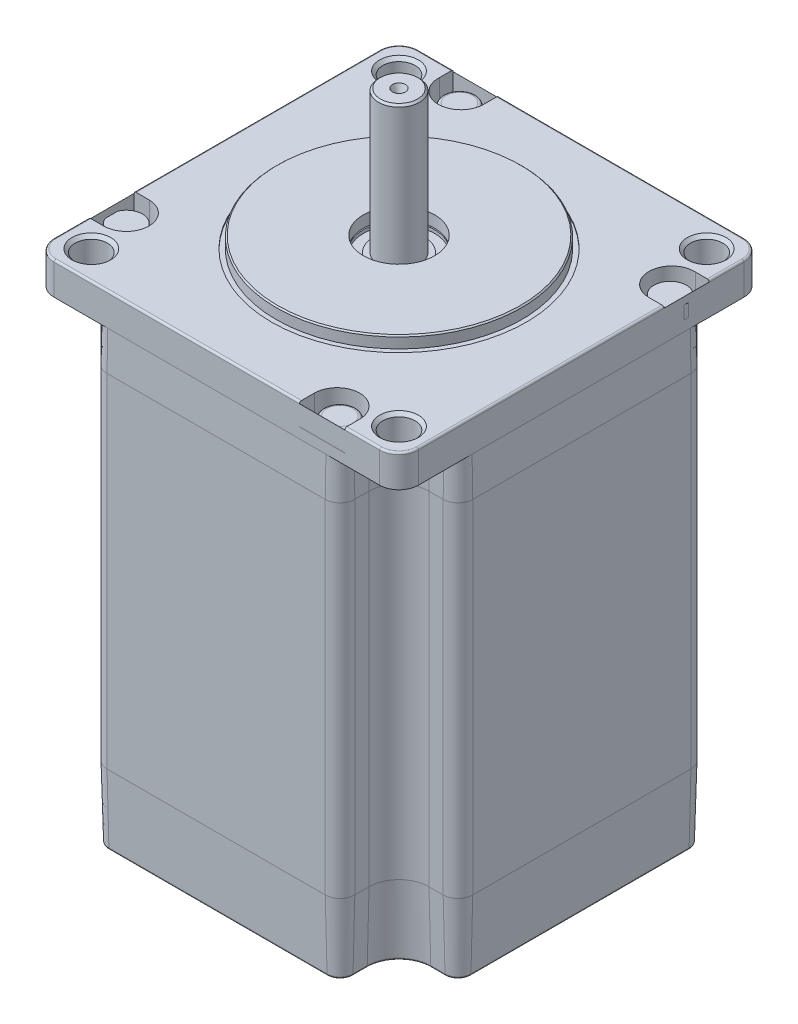
SolidWorks part; units mm, degrees
ref_plane "Спереди" through (0, 0, 0) normal (0, 0, 1) x (1, 0, 0)
ref_plane "Сверху" through (0, 0, 0) normal (0, 1, 0) x (1, 0, 0)
ref_plane "Справа" through (0, 0, 0) normal (1, 0, 0) x (0, 0, -1)
sketch "Эскиз1" plane through (0, 0, 0) normal (0, 1, 0) x (1, 0, 0)
  line L0 (0, 33.8984) -> (0, -32.5387) construction
  line L1 (-16.8775, 28) -> (16.8775, 28)
  line L2 (-28, 16.8775) -> (-28, -16.8775)
  line L3 (-16.8775, -28) -> (16.8775, -28)
  line L4 (28, 16.8775) -> (28, -16.8775)
  line L5 (-28, 28) -> (28, -28) construction
  line L6 (-28, -28) -> (28, 28) construction
  line L7 (-36.1503, 0) -> (41.6733, 0) construction
  line L8 (-18.8775, 23.8) -> (-18.8775, 26)
  line L9 (-23.8, 18.8775) -> (-26, 18.8775)
  line L10 (18.8775, 23.8) -> (18.8775, 26)
  line L11 (23.8, 18.8775) -> (26, 18.8775)
  line L12 (23.8, -18.8775) -> (26, -18.8775)
  line L13 (18.8775, -23.8) -> (18.8775, -26)
  line L14 (-18.8775, -23.8) -> (-18.8775, -26)
  line L15 (-23.8, -18.8775) -> (-26, -18.8775)
  arc A0 (-18.8775, 26) -> (-16.8775, 28) centre (-16.8775, 26) cw
  arc A2 (18.8775, 23.8) -> (23.8, 18.8775) centre (23.8, 23.8) ccw
  arc A3 (-18.8775, 23.8) -> (-23.8, 18.8775) centre (-23.8, 23.8) cw
  arc A5 (18.8775, -23.8) -> (23.8, -18.8775) centre (23.8, -23.8) cw
  arc A6 (-18.8775, -23.8) -> (-23.8, -18.8775) centre (-23.8, -23.8) ccw
  arc A9 (18.8775, 26) -> (16.8775, 28) centre (16.8775, 26) ccw
  arc A10 (26, 18.8775) -> (28, 16.8775) centre (26, 16.8775) cw
  arc A11 (26, -18.8775) -> (28, -16.8775) centre (26, -16.8775) ccw
  arc A12 (18.8775, -26) -> (16.8775, -28) centre (16.8775, -26) cw
  arc A13 (-18.8775, -26) -> (-16.8775, -28) centre (-16.8775, -26) ccw
  arc A14 (-26, -18.8775) -> (-28, -16.8775) centre (-26, -16.8775) cw
  arc A15 (-26, 18.8775) -> (-28, 16.8775) centre (-26, 16.8775) ccw
  point P0 (0, 0)
  point P36 (-18.8775, 28)
  point P39 (18.8775, 28)
  point P46 (18.8775, -28)
  point P49 (-18.8775, -28)
  point P52 (-28, -18.8775)
  point P55 (-28, 18.8775)
  dimension "D3" = 2
  dimension "D1" = 56
  dimension "D2" = 56
  dimension "D6" = 4.2
extrude "Бобышка-Вытянуть4" add sketch "Эскиз1" along normal blind 11 draft 1.5 draft outward yes
sketch "Эскиз8" plane through (0, 11, 0) normal (0, 1, 0) x (1, 0, 0)
  line L0 (-23.8, 19.1655) -> (-26, 19.1655) construction
  line L1 (-19.1655, 26) -> (-19.1655, 23.8) construction
  line L2 (16.8775, 28.288) -> (-16.8775, 28.288) construction
  line L3 (-28.288, 16.8775) -> (-28.288, -16.8775) construction
  line L4 (-26, -19.1655) -> (-23.8, -19.1655) construction
  line L5 (-19.1655, -23.8) -> (-19.1655, -26) construction
  line L6 (-16.8775, -28.288) -> (16.8775, -28.288) construction
  line L7 (19.1655, -26) -> (19.1655, -23.8) construction
  line L8 (23.8, -19.1655) -> (26, -19.1655) construction
  line L9 (28.288, -16.8775) -> (28.288, 16.8775) construction
  line L10 (26, 19.1655) -> (23.8, 19.1655) construction
  line L11 (19.1655, 23.8) -> (19.1655, 26) construction
  line L12 (-23.8, 19.1655) -> (-26, 19.1655)
  line L13 (-19.1655, 26) -> (-19.1655, 23.8)
  line L14 (16.8775, 28.288) -> (-16.8775, 28.288)
  line L15 (-28.288, 16.8775) -> (-28.288, -16.8775)
  line L16 (-26, -19.1655) -> (-23.8, -19.1655)
  line L17 (-19.1655, -23.8) -> (-19.1655, -26)
  line L18 (-16.8775, -28.288) -> (16.8775, -28.288)
  line L19 (19.1655, -26) -> (19.1655, -23.8)
  line L20 (23.8, -19.1655) -> (26, -19.1655)
  line L21 (28.288, -16.8775) -> (28.288, 16.8775)
  line L22 (26, 19.1655) -> (23.8, 19.1655)
  line L23 (19.1655, 23.8) -> (19.1655, 26)
  arc A0 (-26, 19.1655) -> (-28.288, 16.8775) centre (-26, 16.8775) ccw construction
  arc A1 (-23.8, 19.1655) -> (-19.1655, 23.8) centre (-23.8, 23.8) ccw construction
  arc A2 (-16.8775, 28.288) -> (-19.1655, 26) centre (-16.8775, 26) ccw construction
  arc A3 (-28.288, -16.8775) -> (-26, -19.1655) centre (-26, -16.8775) ccw construction
  arc A4 (-19.1655, -23.8) -> (-23.8, -19.1655) centre (-23.8, -23.8) ccw construction
  arc A5 (-19.1655, -26) -> (-16.8775, -28.288) centre (-16.8775, -26) ccw construction
  arc A6 (16.8775, -28.288) -> (19.1655, -26) centre (16.8775, -26) ccw construction
  arc A7 (23.8, -19.1655) -> (19.1655, -23.8) centre (23.8, -23.8) ccw construction
  arc A8 (26, -19.1655) -> (28.288, -16.8775) centre (26, -16.8775) ccw construction
  arc A9 (28.288, 16.8775) -> (26, 19.1655) centre (26, 16.8775) ccw construction
  arc A10 (19.1655, 23.8) -> (23.8, 19.1655) centre (23.8, 23.8) ccw construction
  arc A11 (19.1655, 26) -> (16.8775, 28.288) centre (16.8775, 26) ccw construction
  arc A12 (-26, 19.1655) -> (-28.288, 16.8775) centre (-26, 16.8775) ccw
  arc A13 (-23.8, 19.1655) -> (-19.1655, 23.8) centre (-23.8, 23.8) ccw
  arc A14 (-16.8775, 28.288) -> (-19.1655, 26) centre (-16.8775, 26) ccw
  arc A15 (-28.288, -16.8775) -> (-26, -19.1655) centre (-26, -16.8775) ccw
  arc A16 (-19.1655, -23.8) -> (-23.8, -19.1655) centre (-23.8, -23.8) ccw
  arc A17 (-19.1655, -26) -> (-16.8775, -28.288) centre (-16.8775, -26) ccw
  arc A18 (16.8775, -28.288) -> (19.1655, -26) centre (16.8775, -26) ccw
  arc A19 (23.8, -19.1655) -> (19.1655, -23.8) centre (23.8, -23.8) ccw
  arc A20 (26, -19.1655) -> (28.288, -16.8775) centre (26, -16.8775) ccw
  arc A21 (28.288, 16.8775) -> (26, 19.1655) centre (26, 16.8775) ccw
  arc A22 (19.1655, 23.8) -> (23.8, 19.1655) centre (23.8, 23.8) ccw
  arc A23 (19.1655, 26) -> (16.8775, 28.288) centre (16.8775, 26) ccw
extrude "Бобышка-Вытянуть9" add sketch "Эскиз8" along normal blind 53
fillet "Скругление2" radius 0.3 24 edges at (-24.9, 0, -18.8775) (-27.4142, 0, -18.2917) (-28, 0, 0) (-27.4142, 0, 18.2917) (-24.9, 0, 18.8775) (-20.3193, 0, 20.3193) (-18.8775, 0, 24.9) (-18.2917, 0, 27.4142) (0, 0, 28) (18.2917, 0, 27.4142) (18.8775, 0, 24.9) (20.3193, 0, 20.3193) (24.9, 0, 18.8775) (27.4142, 0, 18.2917) (28, 0, 0) (27.4142, 0, -18.2917) (24.9, 0, -18.8775) (20.3193, 0, -20.3193) (18.8775, 0, -24.9) (18.2917, 0, -27.4142) (0, 0, -28) (-18.2917, 0, -27.4142) (-18.8775, 0, -24.9) (-20.3193, 0, -20.3193)
sketch "Эскиз9" plane through (0, 0, 0) normal (0, -1, 0) x (1, 0, 0)
  circle A0 centre (0, 0) radius 5.5
  dimension "D1" = 11
extrude "Вырез-Вытянуть2" cut sketch "Эскиз9" against normal blind 2
sketch "Эскиз10" plane through (0, 0, 0) normal (0, -1, 0) x (1, 0, 0)
  circle A0 centre (0, 0) radius 12.5
  dimension "D1" = 25
extrude "Вырез-Вытянуть3" cut sketch "Эскиз10" against normal blind 3 from offset 2 offset against normal yes
sketch "Эскиз11" plane through (0, 5, 0) normal (0, -1, 0) x (1, 0, 0)
  circle A0 centre (0, 0) radius 5.6
  circle A1 centre (0, 0) radius 5.5
  dimension "D1" = 11.2
  dimension "D2" = 11
extrude "Вырез-Вытянуть5" cut sketch "Эскиз11" against normal blind 0.2 draft 5
sketch "Эскиз12" plane through (0, 5, 0) normal (0, -1, 0) x (1, 0, 0)
  circle A0 centre (0, 0) radius 3.175
  dimension "D1" = 6.35
extrude "Вырез-Вытянуть6" cut sketch "Эскиз12" against normal blind 0.2
sketch "Эскиз15" plane through (0, 64, 0) normal (0, 1, 0) x (1, 0, 0)
  line L1 (-28.25, 28.25) -> (28.25, 28.25)
  line L2 (-28.25, 28.25) -> (-28.25, -28.25)
  line L3 (-28.25, -28.25) -> (28.25, -28.25)
  line L4 (28.25, 28.25) -> (28.25, -28.25)
  line L5 (-28.25, 28.25) -> (28.25, -28.25) construction
  line L6 (-28.25, -28.25) -> (28.25, 28.25) construction
  point P0 (0, 0)
  dimension "D1" = 56.5
  dimension "D2" = 56.5
sketch "Эскиз16" plane through (0, 64, 0) normal (0, 1, 0) x (1, 0, 0)
  line L12 (-28.288, 16.8775) -> (-28.288, -16.8775)
  line L13 (-26, -19.1655) -> (-23.8, -19.1655)
  line L14 (-19.1655, -23.8) -> (-19.1655, -26)
  line L15 (-16.8775, -28.288) -> (16.8775, -28.288)
  line L16 (19.1655, -26) -> (19.1655, -23.8)
  line L17 (23.8, -19.1655) -> (26, -19.1655)
  line L18 (28.288, -16.8775) -> (28.288, 16.8775)
  line L19 (26, 19.1655) -> (23.8, 19.1655)
  line L20 (19.1655, 23.8) -> (19.1655, 26)
  line L21 (16.8775, 28.288) -> (-16.8775, 28.288)
  line L22 (-19.1655, 26) -> (-19.1655, 23.8)
  line L23 (-23.8, 19.1655) -> (-26, 19.1655)
  line L24 (-28.288, 16.8775) -> (-28.288, -16.8775)
  line L25 (-26, -19.1655) -> (-23.8, -19.1655)
  line L26 (-19.1655, -23.8) -> (-19.1655, -26)
  line L27 (-16.8775, -28.288) -> (16.8775, -28.288)
  line L28 (19.1655, -26) -> (19.1655, -23.8)
  line L29 (23.8, -19.1655) -> (26, -19.1655)
  line L30 (28.288, -16.8775) -> (28.288, 16.8775)
  line L31 (26, 19.1655) -> (23.8, 19.1655)
  line L32 (19.1655, 23.8) -> (19.1655, 26)
  line L33 (16.8775, 28.288) -> (-16.8775, 28.288)
  line L34 (-19.1655, 26) -> (-19.1655, 23.8)
  line L35 (-23.8, 19.1655) -> (-26, 19.1655)
  arc A12 (-26, 19.1655) -> (-28.288, 16.8775) centre (-26, 16.8775) ccw
  arc A13 (-28.288, -16.8775) -> (-26, -19.1655) centre (-26, -16.8775) ccw
  arc A14 (-19.1655, -23.8) -> (-23.8, -19.1655) centre (-23.8, -23.8) ccw
  arc A15 (-19.1655, -26) -> (-16.8775, -28.288) centre (-16.8775, -26) ccw
  arc A16 (16.8775, -28.288) -> (19.1655, -26) centre (16.8775, -26) ccw
  arc A17 (23.8, -19.1655) -> (19.1655, -23.8) centre (23.8, -23.8) ccw
  arc A18 (26, -19.1655) -> (28.288, -16.8775) centre (26, -16.8775) ccw
  arc A19 (28.288, 16.8775) -> (26, 19.1655) centre (26, 16.8775) ccw
  arc A20 (19.1655, 23.8) -> (23.8, 19.1655) centre (23.8, 23.8) ccw
  arc A21 (19.1655, 26) -> (16.8775, 28.288) centre (16.8775, 26) ccw
  arc A22 (-16.8775, 28.288) -> (-19.1655, 26) centre (-16.8775, 26) ccw
  arc A23 (-23.8, 19.1655) -> (-19.1655, 23.8) centre (-23.8, 23.8) ccw
  arc A24 (-26, 19.1655) -> (-28.288, 16.8775) centre (-26, 16.8775) ccw
  arc A25 (-28.288, -16.8775) -> (-26, -19.1655) centre (-26, -16.8775) ccw
  arc A26 (-19.1655, -23.8) -> (-23.8, -19.1655) centre (-23.8, -23.8) ccw
  arc A27 (-19.1655, -26) -> (-16.8775, -28.288) centre (-16.8775, -26) ccw
  arc A28 (16.8775, -28.288) -> (19.1655, -26) centre (16.8775, -26) ccw
  arc A29 (23.8, -19.1655) -> (19.1655, -23.8) centre (23.8, -23.8) ccw
  arc A30 (26, -19.1655) -> (28.288, -16.8775) centre (26, -16.8775) ccw
  arc A31 (28.288, 16.8775) -> (26, 19.1655) centre (26, 16.8775) ccw
  arc A32 (19.1655, 23.8) -> (23.8, 19.1655) centre (23.8, 23.8) ccw
  arc A33 (19.1655, 26) -> (16.8775, 28.288) centre (16.8775, 26) ccw
  arc A34 (-16.8775, 28.288) -> (-19.1655, 26) centre (-16.8775, 26) ccw
  arc A35 (-23.8, 19.1655) -> (-19.1655, 23.8) centre (-23.8, 23.8) ccw
  dimension "D1" = 0
extrude "Бобышка-Вытянуть11" add sketch "Эскиз16" along normal blind 6 draft 1
sketch "Эскиз18" plane through (0, 70, 0) normal (0, 1, 0) x (1, 0, 0)
  line L1 (-28.185, 28.185) -> (28.185, 28.185)
  line L2 (-28.185, 28.185) -> (-28.185, -28.185)
  line L3 (-28.185, -28.185) -> (28.185, -28.185)
  line L4 (28.185, 28.185) -> (28.185, -28.185)
  line L5 (-28.185, 28.185) -> (28.185, -28.185) construction
  line L6 (-28.185, -28.185) -> (28.185, 28.185) construction
  point P0 (0, 0)
  dimension "D1" = 56.37
  dimension "D2" = 56.37
extrude "Бобышка-Вытянуть12" add sketch "Эскиз18" along normal blind 5
fillet "Скругление3" radius 3 4 edges
sketch "Эскиз19" plane through (0, 75, 0) normal (0, 1, 0) x (1, 0, 0)
  circle A0 centre (-23.8, 23.8) radius 2.5
  circle A1 centre (23.8, 23.8) radius 2.5
  circle A2 centre (23.8, -23.8) radius 2.5
  circle A3 centre (-23.8, -23.8) radius 2.5
  dimension "D1" = 5
  dimension "D2" = 5
  dimension "D3" = 5
  dimension "D4" = 5
fillet "Скругление4" radius 0.3 8 edges at (27.3063, 75, -27.3063) (28.185, 75, 0) (27.3063, 75, 27.3063) (0, 75, 28.185) (-27.3063, 75, 27.3063) (-28.185, 75, 0) (-27.3063, 75, -27.3063) (0, 75, -28.185)
hole_wizard "Зенковка для  винта с плоской головкой M51" positions "Эскиз21" profile "Эскиз20" countersink size "M5" standard "Ansi Metric" end condition up to next
sketch "Эскиз21" plane through (0, 75, 0) normal (0, 1, 0) x (1, 0, 0)
  point P0 (-23.8, -23.8)
  point P3 (23.8, -23.8)
  point P6 (23.8, 23.8)
  point P9 (-23.8, 23.8)
sketch "Эскиз20" plane through (-23.8, 75, 23.8) normal (1, 0, 0) x (0, 0, 1)
  line L0 (0, 0) -> (0, 5)
  line L1 (0, 5) -> (2.5, 5)
  line L2 (2.5, 5) -> (2.5, 0.5)
  line L3 (2.5, 0.5) -> (3, 0)
  line L5 (3, 0) -> (0, 0)
  line L6 (-2.5, 0.5) -> (-3, 0) construction
  line L11 (0, -6.35) -> (0, 107.95) construction
  dimension "Диаметр сквозного отверстия" = 5
  dimension "Глубина сквозного отверстия" = 5
  dimension "Диаметр передней зенковки" = 6
  dimension "Угол передней зенковки" = 90
sketch "Эскиз22" plane through (0, 75, 0) normal (0, 1, 0) x (1, 0, 0)
  circle A0 centre (0, 0) radius 19
  dimension "D1" = 38
extrude "Бобышка-Вытянуть13" add sketch "Эскиз22" along normal blind 1.8
chamfer "Фаска1" distance 0.2 angle 45 1 edges at (0, 76.8, 19)
sketch "Эскиз23" plane through (0, 75, 0) normal (0, 1, 0) x (1, 0, 0)
  circle A2 centre (0, 0) radius 19.7
  circle A3 centre (0, 0) radius 19.7
  dimension "D1" = 0.7
extrude "Вырез-Вытянуть11" cut sketch "Эскиз23" against normal blind 0.2
sketch "Эскиз24" plane through (0, 76.8, 0) normal (0, 1, 0) x (1, 0, 0)
  circle A0 centre (0, 0) radius 5.5
  dimension "D1" = 11
extrude "Вырез-Вытянуть12" cut sketch "Эскиз24" against normal blind 2.5
sketch "Эскиз25" plane through (0, 74.3, 0) normal (0, 1, 0) x (1, 0, 0)
  circle A0 centre (0, 0) radius 4
  dimension "D1" = 8
extrude "Бобышка-Вытянуть14" add sketch "Эскиз25" along normal blind 0.2
sketch "Эскиз26" plane through (0, 74.5, 0) normal (0, 1, 0) x (1, 0, 0)
  circle A0 centre (0, 0) radius 3.175
  dimension "D1" = 6.35
extrude "Бобышка-Вытянуть15" add sketch "Эскиз26" along normal blind 22
sketch "Эскиз27" plane through (0, 96.5, 0) normal (0, 1, 0) x (1, 0, 0)
  circle A0 centre (0, 0) radius 1
  dimension "D1" = 2
extrude "Вырез-Вытянуть13" cut sketch "Эскиз27" against normal blind 2 draft 22
sketch "Эскиз28" plane through (0, 5.2, 0) normal (0, -1, 0) x (1, 0, 0)
  circle A0 centre (0, 0) radius 1
  dimension "D1" = 2
extrude "Вырез-Вытянуть14" cut sketch "Эскиз28" against normal blind 2 draft 22
sketch "Эскиз32" plane through (0, 75, 0) normal (0, 1, 0) x (1, 0, 0)
  line L0 (28.1842, 16.8775) -> (28.185, 25.185) construction
  line L1 (12.797, -28.1845) -> (19.8, -28.1845)
  line L2 (12.797, -25.885) -> (12.797, -28.1845)
  line L3 (19.8, -25.885) -> (19.8, -28.1845)
  line L4 (-16.8775, 28.1842) -> (-25.185, 28.185) construction
  line L5 (16.8775, -28.1842) -> (25.185, -28.185) construction
  line L6 (27.885, -25.185) -> (27.885, 25.185) construction
  line L7 (25.185, 27.885) -> (-25.185, 27.885) construction
  line L8 (-27.885, 25.185) -> (-27.885, -25.185) construction
  line L9 (-28.1842, -16.8775) -> (-28.185, -25.185) construction
  line L10 (-26.0352, -19.8049) -> (-28.1845, -19.8049)
  line L11 (-12.7895, 25.8052) -> (-12.7895, 28.1845)
  line L12 (-12.7895, 28.1845) -> (-19.8, 28.1845)
  line L13 (-19.8, 26.0352) -> (-19.8, 28.1845)
  line L14 (-25.185, -27.885) -> (25.185, -27.885) construction
  line L15 (28.1845, 19.8049) -> (28.1845, 12.7943)
  line L16 (25.8029, 12.7943) -> (28.1845, 12.7943)
  line L17 (26.0352, 19.8049) -> (28.1845, 19.8049)
  line L18 (-28.1845, -19.8049) -> (-28.1845, -12.7943)
  line L19 (-25.8029, -12.7943) -> (-28.1845, -12.7943)
  arc A0 (19.8, -25.885) -> (12.797, -25.885) centre (16.2985, -25.885) ccw
  arc A2 (-25.8029, -12.7943) -> (-26.0352, -19.8049) centre (-25.885, -16.3007) cw
  arc A3 (-19.8, 26.0352) -> (-12.7895, 25.8052) centre (-16.2958, 25.8873) ccw
  arc A4 (25.8029, 12.7943) -> (26.0352, 19.8049) centre (25.885, 16.3007) cw
  dimension "D1" = 0
  dimension "D2" = 1.9977
  dimension "D3" = 2
  dimension "D4" = 0
  dimension "D5" = 0
  dimension "D6" = 2
  dimension "D7" = 0
  dimension "D8" = 2
extrude "Вырез-Вытянуть15" cut sketch "Эскиз32" against normal blind 3.4
sketch "Эскиз33" plane through (0, 0, 0) normal (0, -1, 0) x (1, 0, 0)
  circle A0 centre (16.5192, 25.6991) radius 1.3951
  circle A1 centre (25.7376, -16.6007) radius 1.3951
  circle A2 centre (-16.6458, -25.7757) radius 1.3951
  circle A3 centre (-25.741, 16.6519) radius 1.3951
extrude "Вырез-Вытянуть18" cut sketch "Эскиз33" against normal blind 2
sketch "Эскиз34" plane through (0, 71.6, 0) normal (0, 1, 0) x (1, 0, 0)
  circle A0 centre (-16.2667, 25.6219) radius 2.5
  circle A1 centre (25.7131, 16.245) radius 2.5
  circle A2 centre (16.4294, -25.5829) radius 2.5
  circle A3 centre (-25.885, -16.3007) radius 2.5
  dimension "D1" = 5
  dimension "D2" = 5
  dimension "D3" = 5
  dimension "D4" = 5
extrude "Бобышка-Вытянуть16" add sketch "Эскиз34" along normal blind 2
fillet "Скругление5" radius 0.5 2 edges at (-16.2667, 73.6, -23.1219) (16.4294, 73.6, 28.0829)
chamfer "Фаска2" distance 0.3 angle 45 1 edges at (0, 96.5, 3.175)
